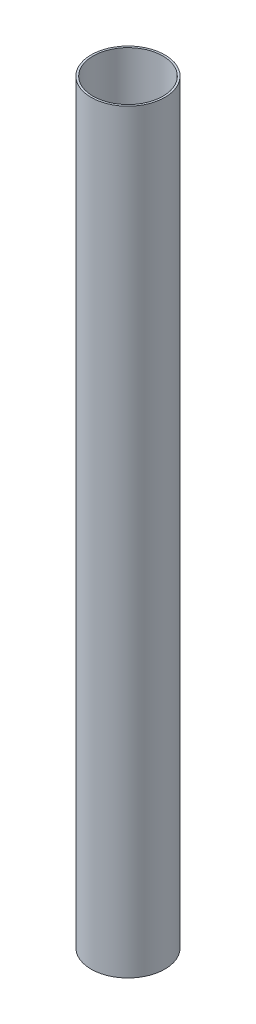
SolidWorks part; units mm, degrees
ref_plane "Front Plane" through (0, 0, 0) normal (0, 0, 1) x (1, 0, 0)
ref_plane "Top Plane" through (0, 0, 0) normal (0, 1, 0) x (1, 0, 0)
ref_plane "Right Plane" through (0, 0, 0) normal (1, 0, 0) x (0, 0, -1)
sketch "Sketch1" plane through (0, 0, 0) normal (0, 1, 0) x (1, 0, 0)
  circle A0 centre (0, 0) radius 25.4
  dimension "D1" = 50.8
extrude "Extrude-Thin1" add sketch "Sketch1" along normal blind 520.192 thin thin type one direction reverse wall 1.3462
